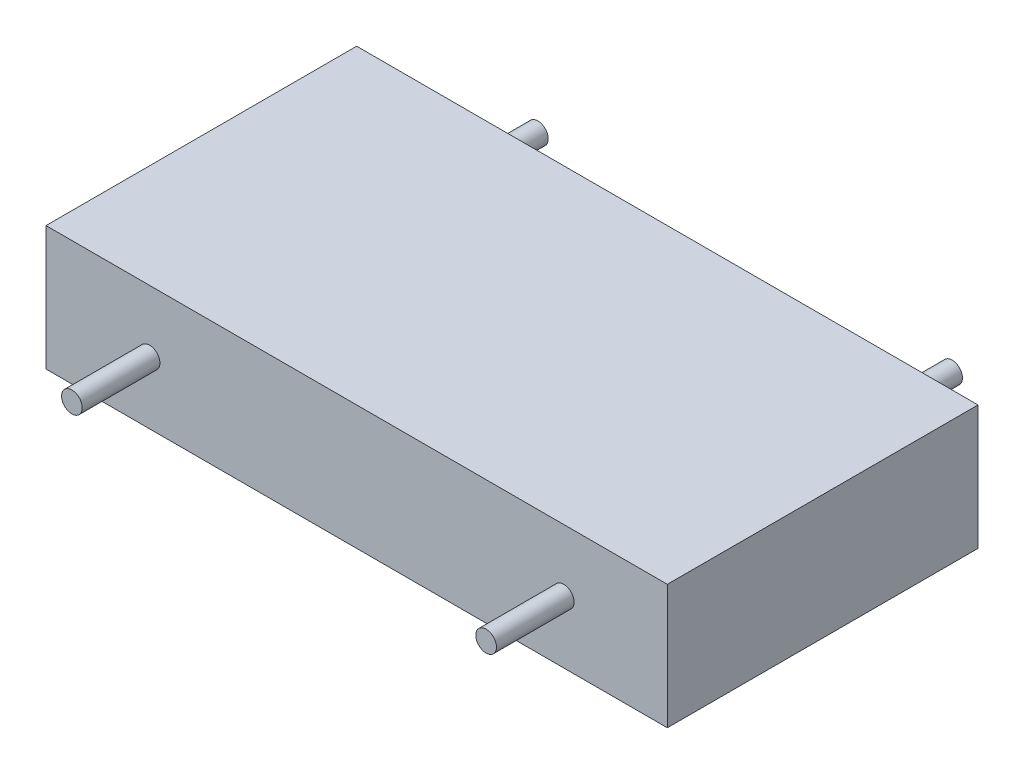
SolidWorks part; units mm, degrees
ref_plane "Front Plane" through (0, 0, 0) normal (0, 0, 1) x (1, 0, 0)
ref_plane "Top Plane" through (0, 0, 0) normal (0, 1, 0) x (1, 0, 0)
ref_plane "Right Plane" through (0, 0, 0) normal (1, 0, 0) x (0, 0, -1)
sketch "Sketch1" plane through (0, 0, 0) normal (0, 1, 0) x (1, 0, 0)
  line L1 (-300, -150) -> (300, -150)
  line L2 (-300, -150) -> (-300, 150)
  line L3 (-300, 150) -> (300, 150)
  line L4 (300, -150) -> (300, 150)
  line L5 (-300, -150) -> (300, 150) construction
  line L6 (-300, 150) -> (300, -150) construction
  point P0 (0, 0)
extrude "Boss-Extrude1" add sketch "Sketch1" along normal blind 120
sketch "Sketch2" plane through (0, 0, -150) normal (0, 0, -1) x (-1, 0, 0)
  circle A0 centre (-200, 60) radius 10
  circle A1 centre (200, 60) radius 10
sketch "Sketch3" plane through (0, 0, 150) normal (0, 0, 1) x (1, 0, 0)
  circle A0 centre (-200, 60) radius 10
  circle A1 centre (200, 60) radius 10
extrude "Boss-Extrude3" add sketch "Sketch3" along normal blind 75 contours A1 | A0
extrude "Boss-Extrude4" add sketch "Sketch2" along normal blind 75 contours A0 | A1
